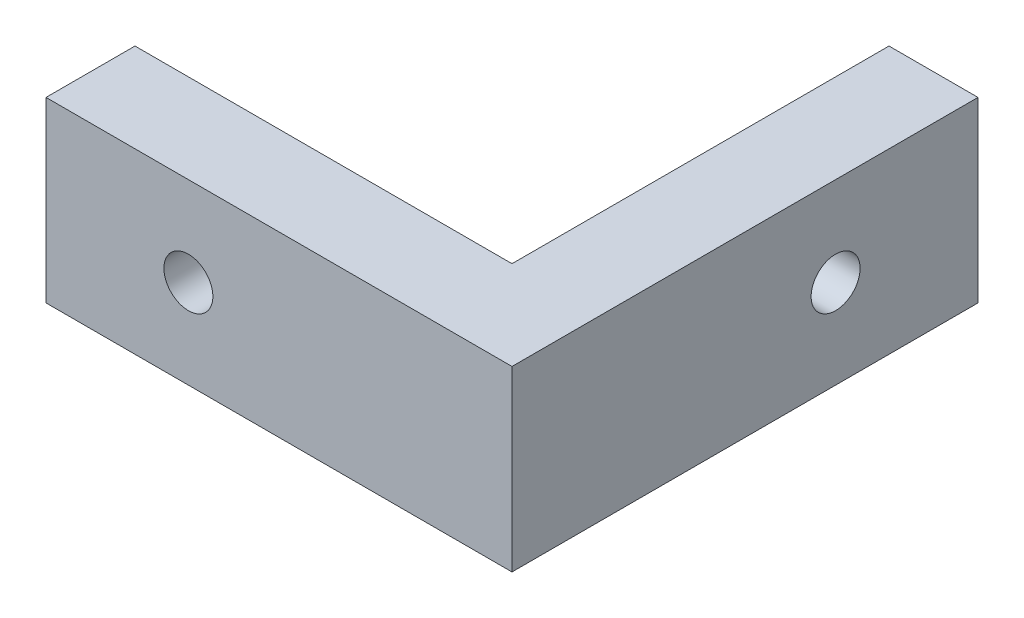
SolidWorks part; units mm, degrees
ref_plane "Front Plane" through (0, 0, 0) normal (0, 0, 1) x (1, 0, 0)
ref_plane "Top Plane" through (0, 0, 0) normal (0, 1, 0) x (1, 0, 0)
ref_plane "Right Plane" through (0, 0, 0) normal (1, 0, 0) x (0, 0, -1)
sketch "Sketch2" plane through (0, 0, 0) normal (0, 1, 0) x (1, 0, 0)
  line L1 (0, 0) -> (-26.18, 0)
  line L3 (-5, 5) -> (-26.18, 5)
  line L4 (-26.18, 0) -> (-26.18, 5)
  line L6 (-5, 5) -> (-5, 26.18)
  line L7 (-5, 26.18) -> (0, 26.18)
  line L8 (0, 0) -> (0, 26.18)
  dimension "D1" = 5
  dimension "D2" = 26.18
  dimension "D3" = 26.18
  dimension "D4" = 5
extrude "Boss-Extrude1" add sketch "Sketch2" along normal blind 10
sketch "Sketch3" plane through (0, 0, 0) normal (0, 0, 1) x (1, 0, 0)
  line L4 (-18.18, 2.5) -> (-18.18, 10.8775) construction
  line L5 (-26.18, 10) -> (-26.18, 0) construction
  line L6 (-26.18, 5) -> (0, 5) construction
  line L7 (0, 10) -> (0, 0) construction
  circle A0 centre (-18.18, 5) radius 1.375
  point P7 (-18.18, 5)
  point P10 (0, 0)
  dimension "D2" = 8
extrude "Cut-Extrude2" cut sketch "Sketch3" against normal up to next
sketch "Sketch4" plane through (0, 0, 0) normal (1, 0, 0) x (0, 0, -1)
  line L0 (26.18, 10) -> (26.18, 0) construction
  line L3 (18.18, 5) -> (18.18, 7.5) construction
  line L4 (26.18, 5) -> (0, 5) construction
  line L5 (0, 10) -> (0, 0) construction
  circle A1 centre (18.18, 5) radius 1.375
  point P1 (18.18, 5)
  point P6 (18.18, 2.8159)
  dimension "D3" = 8
extrude "Cut-Extrude3" cut sketch "Sketch4" against normal up to next
